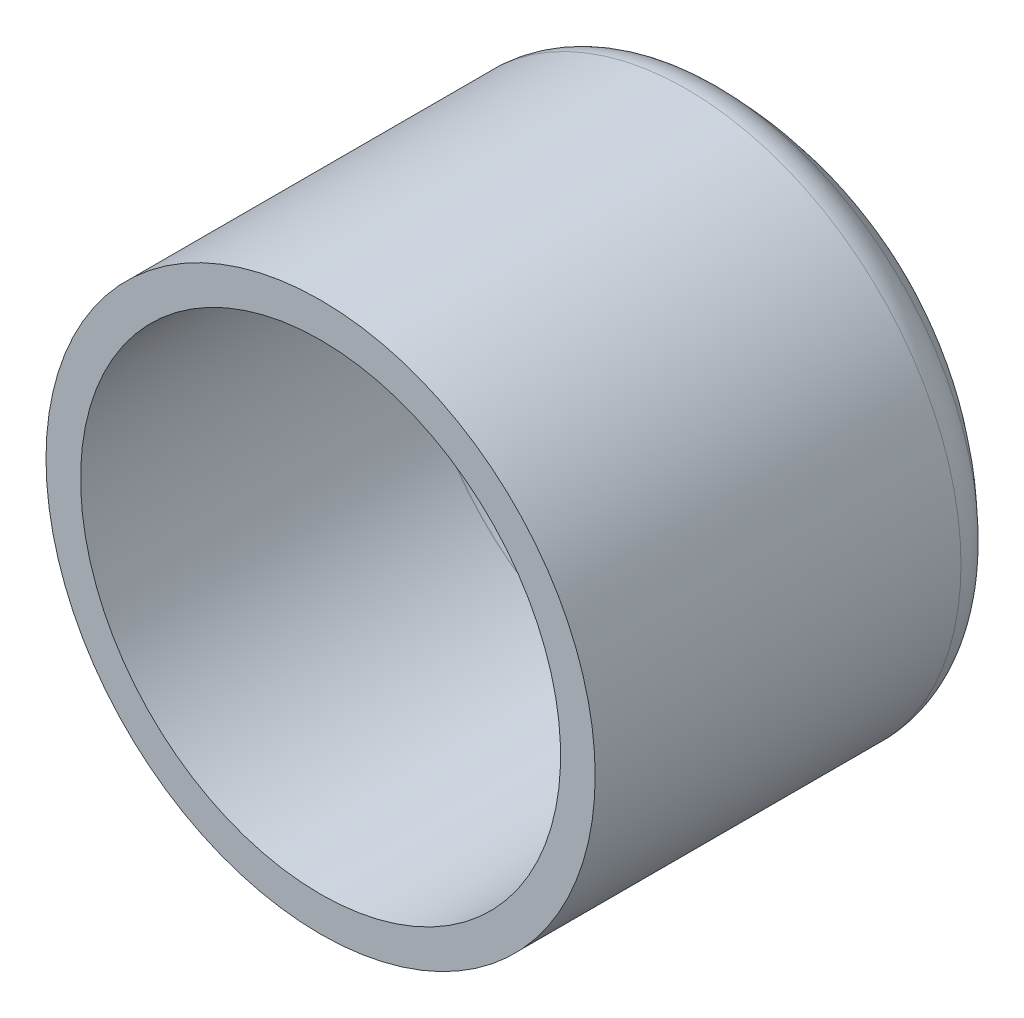
SolidWorks part; units mm, degrees
material "PVC Rigid"
ref_plane "Front Plane" through (0, 0, 0) normal (0, 0, 1) x (1, 0, 0)
ref_plane "Top Plane" through (0, 0, 0) normal (0, 1, 0) x (1, 0, 0)
ref_plane "Right Plane" through (0, 0, 0) normal (1, 0, 0) x (0, 0, -1)
sketch "Sketch1" plane through (0, 0, 0) normal (1, 0, 0) x (0, 0, -1)
  line L0 (-38.4048, 0) -> (38.4048, 0) construction
  line L1 (-38.4048, -36.6903) -> (-38.4048, 36.6903) construction
  line L2 (-38.4048, -36.6903) -> (-38.4048, -41.9735) construction
  line L3 (12.3952, -36.4236) -> (12.3952, 36.4236) construction
  line L4 (12.3952, -36.4236) -> (12.3952, 36.4236) construction
  line L5 (-38.4048, -41.9735) -> (16.7386, -41.9735) construction
  line L6 (-38.4048, 36.6903) -> (-38.4048, 41.9735) construction
  line L7 (-38.4048, 41.9735) -> (16.7386, 41.9735) construction
  line L8 (12.3952, 36.4236) -> (12.4596, 36.4236) construction
  line L9 (12.3952, -36.4236) -> (12.4596, -36.4236) construction
  line L10 (16.7386, -41.9735) -> (20.0887, -41.9735) construction
  line L11 (16.7386, 41.9735) -> (20.0887, 41.9735) construction
  line L12 (-38.4048, -36.6903) -> (12.3952, -36.4236) construction
  line L13 (-38.4048, 36.6903) -> (12.3952, 36.4236) construction
  arc A0 (19.6842, -33.106) -> (19.6842, 33.106) centre (-18.8468, 0) ccw construction
  arc A1 (12.4596, -36.4236) -> (19.6842, -33.106) centre (12.4596, -26.8986) ccw construction
  arc A2 (19.6842, 33.106) -> (12.4596, 36.4236) centre (12.4596, 26.8986) ccw construction
  arc A4 (20.0887, -41.9735) -> (20.0887, 41.9735) centre (-18.8468, 0) ccw construction
  point P0 (31.9532, 0)
  point P4 (0, 0)
  point P9 (-38.4048, 0)
  point P13 (12.3952, 0)
  point P15 (12.3952, 0)
  dimension "Int. Dome Rad" = 50.8
  dimension "Int. Dome Fillet" = 9.525
  dimension "Dome Thickness" = 6.4516
  dimension "Socket to Dome" = 19.558
  dimension "Socket Depth" = 50.8
  dimension "Socket Bottom Dia" = 72.8472
  dimension "Socket Top Dia" = 73.3806
  dimension "Wall Thickness" = 5.2832
  dimension "Ext. Body Length" = 55.1434
sketch "Sketch2" plane through (0, 0, 0) normal (1, 0, 0) x (0, 0, -1)
  line L6 (31.9532, 0) -> (38.4048, 0)
  line L7 (-38.4048, -36.6903) -> (-38.4048, -41.9735)
  line L8 (-38.4048, -41.9735) -> (20.0887, -41.9735)
  line L9 (-38.4048, -36.6903) -> (12.3952, -36.4236)
  line L10 (12.3952, -36.4236) -> (12.4596, -36.4236)
  arc A6 (20.0887, -41.9735) -> (20.0887, 41.9735) centre (-18.8468, 0) ccw construction
  arc A7 (12.4596, -36.4236) -> (19.6842, -33.106) centre (12.4596, -26.8986) ccw construction
  arc A8 (19.6842, -33.106) -> (19.6842, 33.106) centre (-18.8468, 0) ccw construction
  arc A9 (20.0887, -41.9735) -> (38.4048, 0) centre (-18.8468, 0) ccw
  arc A10 (12.4596, -36.4236) -> (19.6842, -33.106) centre (12.4596, -26.8986) ccw
  arc A11 (19.6842, -33.106) -> (31.9532, 0) centre (-18.8468, 0) ccw
revolve "Revolve1" add sketch "Sketch2" angle 360 about L0
fillet "Fillet1" radius 6.35 1 edges at (0, -41.9735, -20.0887)
sketch "Sketch3" plane through (0, 0, 38.4048) normal (0, 0, 1) x (1, 0, 0)
  circle A2 centre (0, 0) radius 36.6903 construction
  circle A3 centre (0, 0) radius 36.6903
  point P3 (-36.6903, 0)
  point P4 (0, 36.6903)
  point P5 (36.6903, 0)
  point P6 (0, -36.6903)
